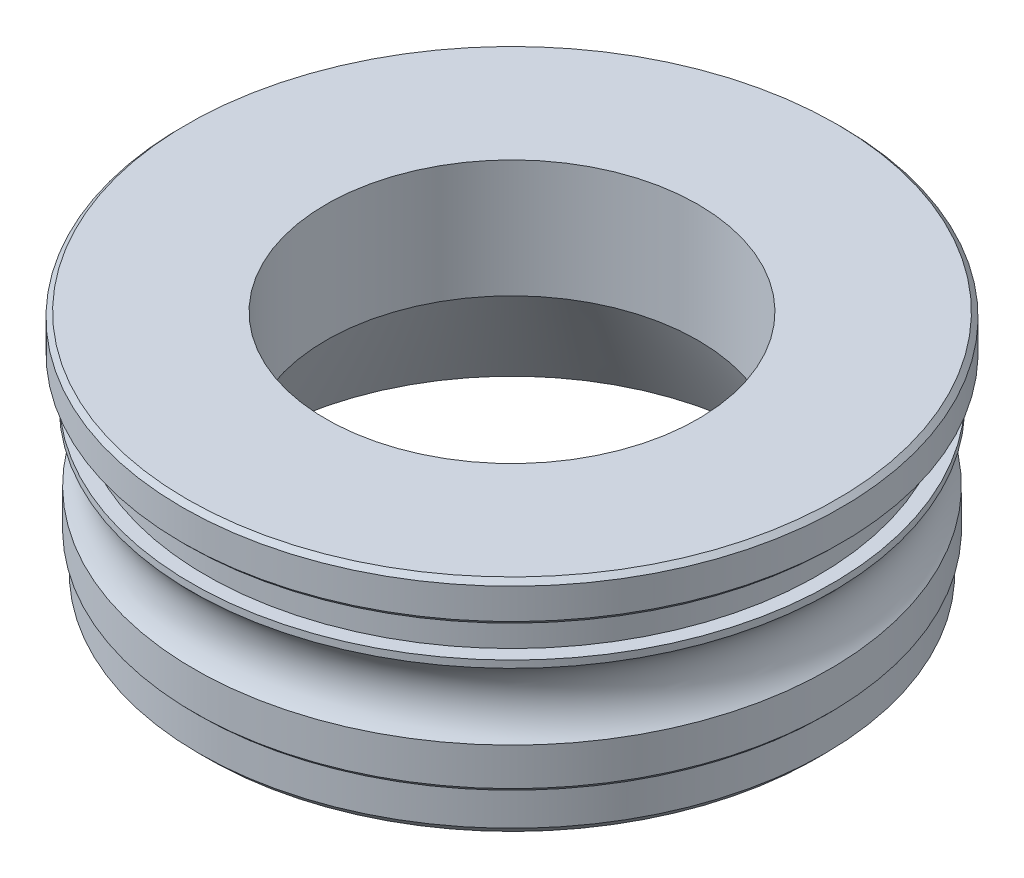
SolidWorks part; units mm, degrees
material "latón"
ref_plane "Alzado" through (0, 0, 0) normal (0, 0, 1) x (1, 0, 0)
ref_plane "Planta" through (0, 0, 0) normal (0, 1, 0) x (1, 0, 0)
ref_plane "Vista lateral" through (0, 0, 0) normal (1, 0, 0) x (0, 0, -1)
sketch "Croquis1" plane through (0, 0, 0) normal (0, 0, 1) x (1, 0, 0)
  line L0 (0, 0) -> (0, 5) construction
  line L1 (6.45, 0) -> (6.65, 0.2)
  line L2 (6.65, 0.2) -> (6.65, 0.9)
  line L3 (6.65, 0.9) -> (6.75, 1)
  line L4 (6.75, 1) -> (6.75, 1.667)
  line L5 (6.75, 1.667) -> (6.75, 1.8)
  line L6 (5.3934, 0) -> (6.45, 0)
  line L7 (3.95, 5) -> (6.9, 5)
  line L8 (6.9, 5) -> (7, 4.9)
  line L9 (7, 4.25) -> (6.9, 4.15)
  line L10 (6.5, 4.15) -> (6.5, 3.4)
  line L11 (6.5, 3.4) -> (6.8, 3.4)
  line L12 (3.95, 5) -> (3.95, 2.5)
  line L13 (3.95, 2.5) -> (5.3934, 0)
  line L14 (7, 4.9) -> (7, 4.25)
  line L15 (6.9, 4.15) -> (6.5, 4.15)
  line L16 (6.8, 3.4) -> (6.8, 3.2477)
  arc A0 (6.8, 3.2477) -> (6.75, 1.8) centre (7.4641, 2.5001) ccw
  point P9 (7, 5)
  point P12 (7, 4.15)
  point P23 (6.8, 3.2477)
  dimension "D9" = 5
  dimension "D8" = 1
  dimension "D10" = 3.05
  dimension "D2" = 0.2
  dimension "D3" = 7.9
  dimension "D4" = 0.7
  dimension "D5" = 0.1
  dimension "D6" = 6.45
  dimension "D7" = 45
  dimension "D11" = 6.5
  dimension "D12" = 2.5
  dimension "D13" = 3.2
  dimension "D14" = 0.3
  dimension "D15" = 1.7523
  dimension "D16" = 30
  dimension "D17" = 3.4
  dimension "D19" = 0.85
  dimension "D20" = 0.25
revolve "Revolución1" add sketch "Croquis1" angle 360 about L0
